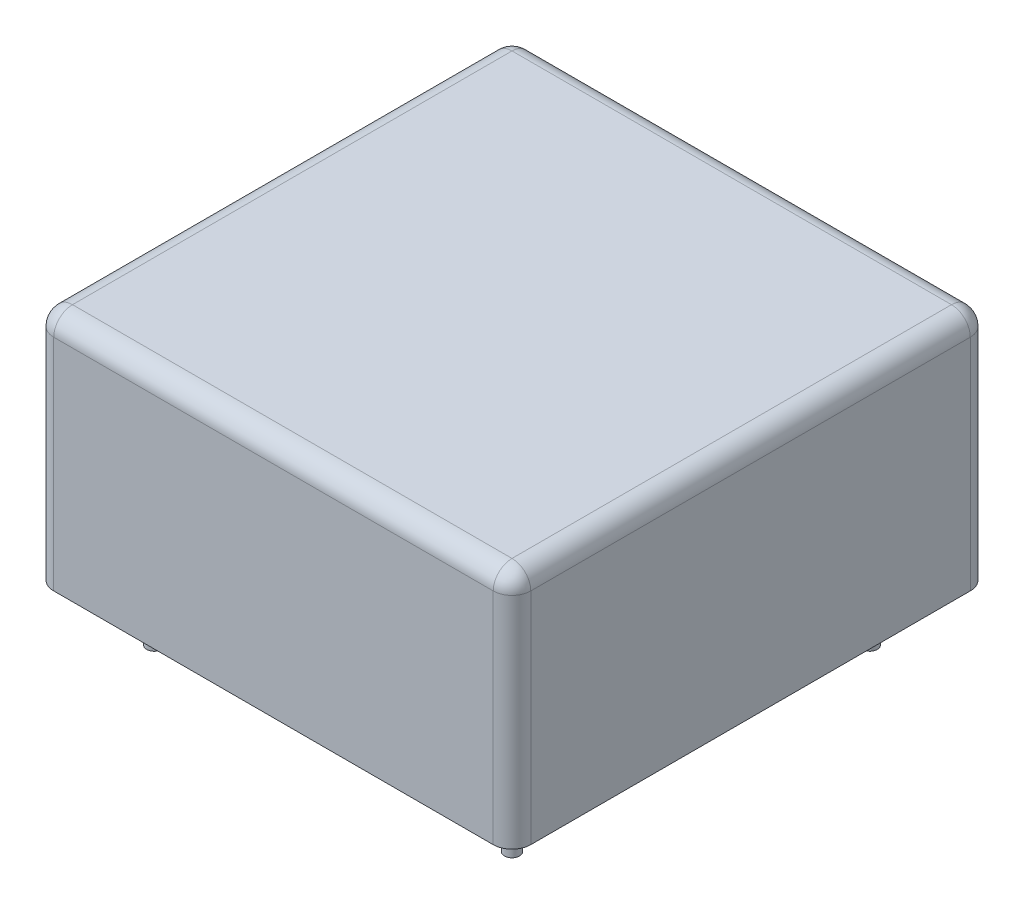
SolidWorks part; units mm, degrees
ref_plane "Спереди" through (0, 0, 0) normal (0, 0, 1) x (1, 0, 0)
ref_plane "Сверху" through (0, 0, 0) normal (0, 1, 0) x (1, 0, 0)
ref_plane "Справа" through (0, 0, 0) normal (1, 0, 0) x (0, 0, -1)
sketch "Эскиз2" plane through (0, 0, 0) normal (0, 1, 0) x (1, 0, 0)
  line L0 (0, 0) -> (9.525, 0) construction
  line L1 (0, 0) -> (0, -19.05) construction
  circle A0 centre (0, 0) radius 0.4
  circle A1 centre (9.525, 0) radius 0.4
  circle A2 centre (0, -19.05) radius 0.4
  circle A3 centre (19.05, -19.05) radius 0.4
  circle A4 centre (19.05, 0) radius 0.4
extrude "Бобышка-Вытянуть1" add sketch "Эскиз2" against normal blind 3
sketch "Эскиз3" plane through (0, 0, 0) normal (0, 1, 0) x (1, 0, 0)
  line L0 (0, 0) -> (19.05, -19.05) construction
  line L1 (19.05, 0) -> (0, -19.05) construction
  line L3 (-2.175, 3.175) -> (21.225, 3.175)
  line L4 (-3.175, 2.175) -> (-3.175, -21.225)
  line L5 (-2.175, -22.225) -> (21.225, -22.225)
  line L6 (22.225, 2.175) -> (22.225, -21.225)
  line L7 (-3.175, 3.175) -> (22.225, -22.225) construction
  line L8 (-3.175, -22.225) -> (22.225, 3.175) construction
  arc A0 (-2.175, 3.175) -> (-3.175, 2.175) centre (-2.175, 2.175) ccw
  arc A1 (-3.175, -21.225) -> (-2.175, -22.225) centre (-2.175, -21.225) ccw
  arc A2 (21.225, -22.225) -> (22.225, -21.225) centre (21.225, -21.225) ccw
  arc A3 (22.225, 2.175) -> (21.225, 3.175) centre (21.225, 2.175) ccw
  point P8 (9.525, -9.525)
  dimension "D1" = 1
  dimension "D2" = 1
extrude "Бобышка-Вытянуть2" add sketch "Эскиз3" along normal blind 12.7
fillet "Скругление1" radius 1 8 edges at (21.9321, 12.7, -2.8821) (22.225, 12.7, 9.525) (21.9321, 12.7, 21.9321) (9.525, 12.7, 22.225) (-2.8821, 12.7, 21.9321) (-3.175, 12.7, 9.525) (-2.8821, 12.7, -2.8821) (9.525, 12.7, -3.175)
